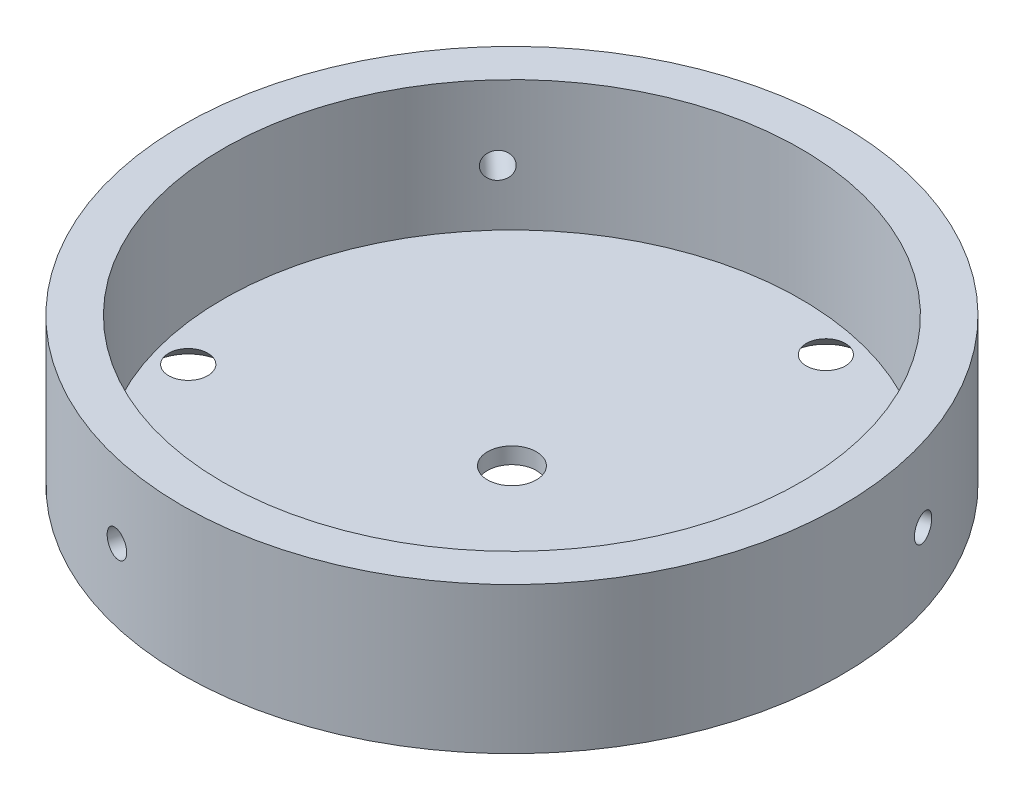
SolidWorks part; units mm, degrees
ref_plane "Front Plane" through (0, 0, 0) normal (0, 0, 1) x (1, 0, 0)
ref_plane "Top Plane" through (0, 0, 0) normal (0, 1, 0) x (1, 0, 0)
ref_plane "Right Plane" through (0, 0, 0) normal (1, 0, 0) x (0, 0, -1)
sketch "Sketch1" plane through (0, 0, 0) normal (0, 1, 0) x (1, 0, 0)
  circle A0 centre (0, 0) radius 20.25
  dimension "D1" = 40.5
extrude "Boss-Extrude1" add sketch "Sketch1" along normal blind 9
sketch "Sketch2" plane through (0, 9, 0) normal (0, 1, 0) x (1, 0, 0)
  circle A0 centre (0, 0) radius 17.75
  dimension "D1" = 35.5
extrude "Cut-Extrude1" cut sketch "Sketch2" against normal blind 8
hole_wizard "CSK SLOT for M2 Countersunk Flat Head Screw1" positions "Sketch3" profile "Sketch4" size "M2" standard "ISO" slot yes
sketch "Sketch3" plane through (0, 0, 0) normal (0, -1, 0) x (-1, 0, 0)
  line L0 (-11.6097, -11.0097) -> (0, 0)
  point P0 (-11.6097, -11.0097)
  dimension "D1" = 16
sketch "Sketch4" plane through (11.6097, 0, 11.0097) normal (1, 0, 0) x (0, 0, -1)
  line L0 (0, 0) -> (0, 6.521)
  line L1 (0, 6.521) -> (1.2, 5.8)
  line L2 (1.2, 5.8) -> (1.2, 1)
  line L3 (1.2, 1) -> (2.2, 0)
  line L5 (2.2, 0) -> (0, 0)
  line L6 (-1.2, 1) -> (-2.2, 0) construction
  line L10 (0, 6.521) -> (-1.2, 5.8) construction
  line L11 (0, -6.35) -> (0, 107.95) construction
  dimension "Hole Dia." = 2.4
  dimension "Hole Depth" = 5.8
  dimension "Near C'Sink Dia." = 4.4
  dimension "Near C'Sink Angle" = 90
  dimension "Drill Angle" = 118
pattern_circular "CirPattern1" count 3 over 360 about axis through (0, 0, 0) along (0, 1, 0) of "CSK SLOT for M2 Countersunk Flat Head Screw1"
sketch "Sketch5" plane through (0, 0, 0) normal (0, -1, 0) x (1, 0, 0)
  circle A0 centre (0, 0) radius 1.5
  dimension "D1" = 3
extrude "Cut-Extrude2" cut sketch "Sketch5" against normal blind 8
hole_wizard "M2 Tapped Hole1" positions "3DSketch1" profile "Sketch6" tap size "M2" standard "ISO"
sketch3d "3DSketch1"
  point P0 (-4.5608, 4.4458, 19.7297)
sketch "Sketch6" plane through (-4.5608, 4.4458, 19.7297) normal (0, 1, 0) x (0.9743, 0, 0.2252)
  line L0 (0, 0) -> (0, 4.9807)
  line L1 (0, 4.9807) -> (0.8, 4.5)
  line L2 (0.8, 4.5) -> (0.8, 0)
  line L5 (0.8, 0) -> (0, 0)
  line L10 (0, 4.9807) -> (-0.8, 4.5) construction
  line L11 (0, -6.35) -> (0, 107.95) construction
  dimension "Tap Drill Dia." = 1.6
  dimension "Tap Drill Depth" = 4.5
  dimension "Drill Angle" = 118
pattern_circular "CirPattern2" count 3 over 360 about axis through (0, 9, 0) along (0, -1, 0) of "M2 Tapped Hole1"
sketch "Sketch7" plane through (0, 0, 0) normal (0, -1, 0) x (1, 0, 0)
  circle A0 centre (0, 0) radius 4.5
  dimension "D1" = 9
extrude "Boss-Extrude3" [suppressed] add sketch "Sketch7" along normal blind 4
sketch "Sketch8" [suppressed] plane through (0, -4, 0) normal (0, -1, 0) x (1, 0, 0)
  circle A0 centre (0, 0) radius 3.265
  dimension "D1" = 6.53
extrude "Cut-Extrude3" [suppressed] cut sketch "Sketch8" against normal blind 4
